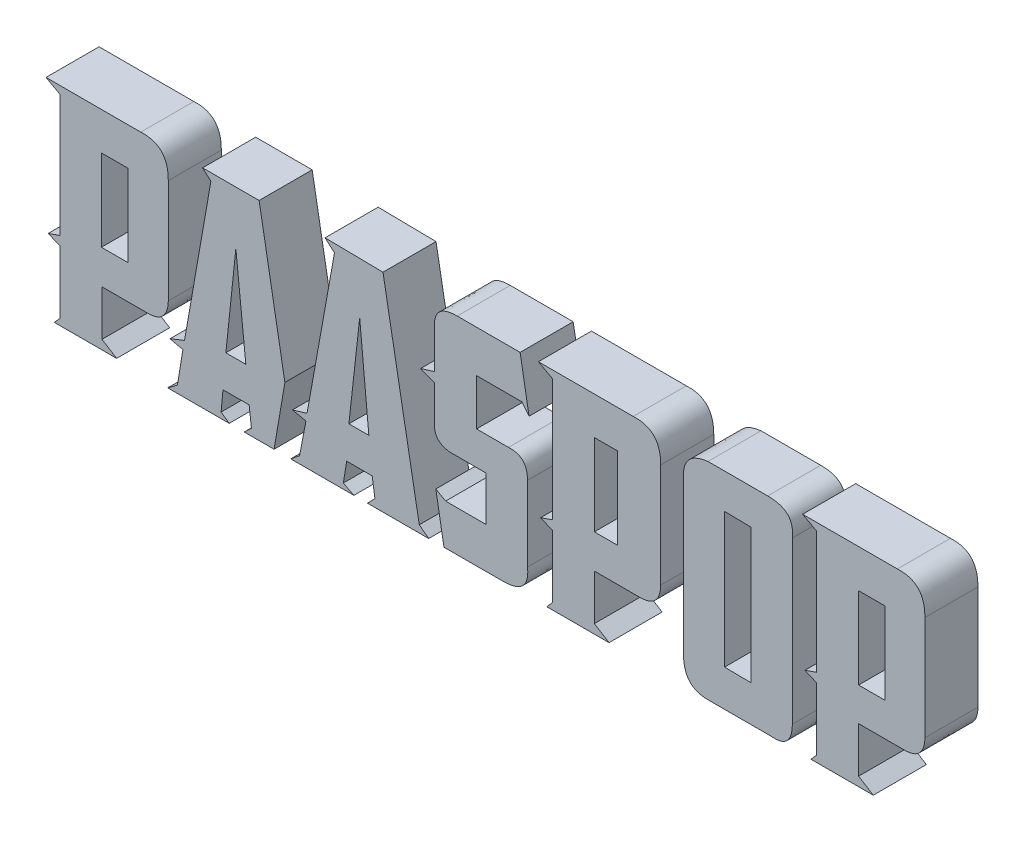
SolidWorks part; units mm, degrees
ref_plane "Front Plane" through (0, 0, 0) normal (0, 0, 1) x (1, 0, 0)
ref_plane "Top Plane" through (0, 0, 0) normal (0, 1, 0) x (1, 0, 0)
ref_plane "Right Plane" through (0, 0, 0) normal (1, 0, 0) x (0, 0, -1)
sketch "Model" plane through (0, 0, 0) normal (0, 0, 1) x (1, 0, 0)
  line L0 (89.8024, -74.6322) -> (88.2702, -65.8873)
  line L1 (88.2702, -65.8873) -> (90.1091, -66.95)
  line L2 (90.1091, -66.95) -> (97.75, -66.95)
  line L3 (97.75, -66.95) -> (97.75, -58.55)
  line L4 (97.75, -58.55) -> (90.9968, -58.55)
  line L5 (87.9813, -48.6879) -> (85.3918, -47.6707)
  line L6 (85.3918, -47.6707) -> (88.05, -46.8495)
  line L7 (88.05, -46.8495) -> (88.05, -39.9178)
  line L8 (104.1551, -35.65) -> (105.839, -45.2393)
  line L9 (105.839, -45.2393) -> (104.4684, -43.55)
  line L10 (104.4684, -43.55) -> (95.95, -43.55)
  line L11 (95.95, -43.55) -> (95.95, -52.25)
  line L12 (95.95, -52.25) -> (101.962, -52.25)
  line L13 (107.6013, -35.45) -> (125.459, -35.45)
  line L14 (118.15, -64.35) -> (118.15, -72.9269)
  line L15 (118.15, -72.9269) -> (120.9162, -74.65)
  line L16 (120.9162, -74.65) -> (109.1678, -74.65)
  line L17 (109.1678, -74.65) -> (110.25, -73.436)
  line L18 (110.25, -73.436) -> (110.25, -61.6483)
  line L19 (110.25, -61.6483) -> (108.0178, -60.7085)
  line L20 (108.0178, -60.7085) -> (110.25, -59.9252)
  line L21 (110.25, -59.9252) -> (110.25, -36.8982)
  line L22 (110.25, -36.8982) -> (107.6013, -35.45)
  line L23 (139.5572, -74.65) -> (151.4623, -74.65)
  line L24 (14.8013, -35.45) -> (32.659, -35.45)
  line L25 (25.35, -64.35) -> (25.35, -72.9269)
  line L26 (25.35, -72.9269) -> (28.1162, -74.65)
  line L27 (28.1162, -74.65) -> (16.3678, -74.65)
  line L28 (16.3678, -74.65) -> (17.45, -73.436)
  line L29 (17.45, -73.436) -> (17.45, -61.6483)
  line L30 (17.45, -61.6483) -> (15.2178, -60.7085)
  line L31 (15.2178, -60.7085) -> (17.45, -59.9252)
  line L32 (17.45, -59.9252) -> (17.45, -36.8982)
  line L33 (17.45, -36.8982) -> (14.8013, -35.45)
  line L34 (157.4013, -35.45) -> (175.259, -35.45)
  line L35 (167.95, -64.35) -> (167.95, -72.9269)
  line L36 (167.95, -72.9269) -> (170.7162, -74.65)
  line L37 (170.7162, -74.65) -> (158.9678, -74.65)
  line L38 (158.9678, -74.65) -> (160.05, -73.436)
  line L39 (160.05, -73.436) -> (160.05, -61.6483)
  line L40 (160.05, -61.6483) -> (157.8178, -60.7085)
  line L41 (157.8178, -60.7085) -> (160.05, -59.9252)
  line L42 (160.05, -59.9252) -> (160.05, -36.8982)
  line L43 (160.05, -36.8982) -> (157.4013, -35.45)
  line L44 (37.737, -74.65) -> (49.3288, -74.65)
  line L45 (49.3288, -74.65) -> (47.8015, -73.5707)
  line L46 (47.8015, -73.5707) -> (48.154, -69.75)
  line L47 (48.154, -69.75) -> (53.0883, -69.75)
  line L48 (53.0883, -69.75) -> (53.5191, -73.3748)
  line L49 (53.5191, -73.3748) -> (52.1485, -74.65)
  line L50 (52.1485, -74.65) -> (57.7877, -74.65)
  line L51 (57.7877, -74.65) -> (59.8241, -62.7257)
  line L52 (59.8241, -62.7257) -> (54.9681, -35.45)
  line L53 (54.9681, -35.45) -> (44.3161, -35.45)
  line L54 (44.3161, -35.45) -> (45.8826, -36.8399)
  line L55 (45.8826, -36.8399) -> (40.9091, -65.3199)
  line L56 (40.9091, -65.3199) -> (38.1678, -66.4213)
  line L57 (38.1678, -66.4213) -> (40.5958, -66.9719)
  line L58 (40.5958, -66.9719) -> (39.5776, -73.2781)
  line L59 (39.5776, -73.2781) -> (37.737, -74.65)
  line L60 (48.7022, -63.45) -> (52.4618, -63.45)
  line L61 (52.4618, -63.45) -> (50.582, -45.4879)
  line L62 (50.582, -45.4879) -> (48.7022, -63.45)
  line L63 (60.9207, -74.65) -> (72.8258, -74.65)
  line L64 (72.8258, -74.65) -> (70.8416, -73.6359)
  line L65 (70.8416, -73.6359) -> (71.4682, -69.75)
  line L66 (71.4682, -69.75) -> (76.272, -69.75)
  line L67 (76.272, -69.75) -> (76.7942, -73.1921)
  line L68 (76.7942, -73.1921) -> (75.3844, -74.65)
  line L69 (75.3844, -74.65) -> (86.924, -74.65)
  line L70 (86.924, -74.65) -> (85.1486, -73.2924)
  line L71 (85.1486, -73.2924) -> (78.3084, -35.4884)
  line L72 (78.3084, -35.4884) -> (67.3954, -35.3317)
  line L73 (67.3954, -35.3317) -> (69.1707, -36.8982)
  line L74 (69.1707, -36.8982) -> (64.0014, -65.6689)
  line L75 (64.0014, -65.6689) -> (61.234, -66.5044)
  line L76 (61.234, -66.5044) -> (63.7925, -67.0265)
  line L77 (63.7925, -67.0265) -> (62.5916, -73.2924)
  line L78 (62.5916, -73.2924) -> (60.9207, -74.65)
  line L79 (71.8859, -63.45) -> (75.6454, -63.45)
  line L80 (75.6454, -63.45) -> (73.9223, -45.1224)
  line L81 (73.9223, -45.1224) -> (71.8859, -63.45)
  line L82 (118.15, -42.55) -> (118.15, -57.95)
  line L83 (118.15, -57.95) -> (122.55, -57.95)
  line L84 (122.55, -57.95) -> (122.55, -42.55)
  line L85 (122.55, -42.55) -> (118.15, -42.55)
  line L86 (142.6901, -67.7519) -> (147.6897, -67.8136)
  line L87 (147.6897, -67.8136) -> (147.6897, -42.4117)
  line L88 (147.6897, -42.4117) -> (142.6901, -42.35)
  line L89 (142.6901, -42.35) -> (142.6901, -67.7519)
  line L90 (25.25, -42.55) -> (25.25, -57.95)
  line L91 (25.25, -57.95) -> (30.25, -57.95)
  line L92 (30.25, -57.95) -> (30.25, -42.55)
  line L93 (30.25, -42.55) -> (25.25, -42.55)
  line L94 (167.95, -42.65) -> (167.95, -58.05)
  line L95 (167.95, -58.05) -> (172.95, -58.05)
  line L96 (172.95, -58.05) -> (172.95, -42.65)
  line L97 (172.95, -42.65) -> (167.95, -42.65)
  spline S0 degree 2 poles (90.9968, -58.55) (88.0205, -58.2803) (87.9813, -55.5389) knots 5 5 5 6 6 6
  spline S1 degree 2 poles (87.9813, -55.5389) (87.9422, -52.7976) (87.9813, -48.6879) knots 6 6 6 7 7 7
  spline S2 degree 2 poles (88.05, -39.9178) (87.5897, -35.65) (92.2891, -35.65) knots 10 10 10 11 11 11
  spline S3 degree 2 poles (92.2891, -35.65) (96.9885, -35.65) (104.1551, -35.65) knots 11 11 11 12 12 12
  spline S4 degree 2 poles (101.962, -52.25) (105.55, -52.0579) (105.55, -55.837) knots 17 17 17 18 18 18
  spline S5 degree 2 poles (105.55, -55.837) (105.55, -59.6161) (105.55, -69.994) knots 18 18 18 19 19 19
  spline S6 degree 2 poles (105.55, -69.994) (106.0665, -74.615) (100.9364, -74.615) knots 19 19 19 20 20 20
  spline S7 degree 2 poles (100.9364, -74.615) (95.8062, -74.615) (89.8024, -74.6322) knots 20 20 20 21 21 21
  spline S8 degree 2 poles (125.459, -35.45) (130.65, -35.1751) (130.65, -40.7752) knots 1 1 1 2 2 2
  spline S9 degree 2 poles (130.65, -40.7752) (130.65, -46.3753) (130.65, -60.3952) knots 2 2 2 3 3 3
  spline S10 degree 2 poles (130.65, -60.3952) (130.55, -64.35) (126.7513, -64.35) knots 3 3 3 4 4 4
  spline S11 degree 2 poles (126.7513, -64.35) (122.9526, -64.35) (118.15, -64.35) knots 4 4 4 5 5 5
  spline S12 degree 2 poles (151.4623, -74.65) (155.45, -75.0544) (155.45, -70.6944) knots 1 1 1 2 2 2
  spline S13 degree 2 poles (155.45, -70.6944) (155.45, -66.3344) (155.45, -40.3311) knots 2 2 2 3 3 3
  spline S14 degree 2 poles (155.45, -40.3311) (156.005, -35.75) (150.8096, -35.75) knots 3 3 3 4 4 4
  spline S15 degree 2 poles (150.8096, -35.75) (145.6142, -35.75) (139.5572, -35.75) knots 4 4 4 5 5 5
  spline S16 degree 2 poles (139.5572, -35.75) (134.95, -36.3105) (134.95, -40.2006) knots 5 5 5 6 6 6
  spline S17 degree 2 poles (134.95, -40.2006) (134.95, -44.0907) (134.95, -69.7807) knots 6 6 6 7 7 7
  spline S18 degree 2 poles (134.95, -69.7807) (135.0666, -74.65) (139.5572, -74.65) knots 7 7 7 8 8 8
  spline S19 degree 2 poles (32.659, -35.45) (37.85, -35.1751) (37.85, -40.7752) knots 1 1 1 2 2 2
  spline S20 degree 2 poles (37.85, -40.7752) (37.85, -46.3753) (37.85, -60.3952) knots 2 2 2 3 3 3
  spline S21 degree 2 poles (37.85, -60.3952) (37.75, -64.35) (33.9513, -64.35) knots 3 3 3 4 4 4
  spline S22 degree 2 poles (33.9513, -64.35) (30.1526, -64.35) (25.35, -64.35) knots 4 4 4 5 5 5
  spline S23 degree 2 poles (175.259, -35.45) (180.45, -35.1751) (180.45, -40.7752) knots 1 1 1 2 2 2
  spline S24 degree 2 poles (180.45, -40.7752) (180.45, -46.3753) (180.45, -60.3952) knots 2 2 2 3 3 3
  spline S25 degree 2 poles (180.45, -60.3952) (180.35, -64.35) (176.5513, -64.35) knots 3 3 3 4 4 4
  spline S26 degree 2 poles (176.5513, -64.35) (172.7526, -64.35) (167.95, -64.35) knots 4 4 4 5 5 5
extrude "Boss-Extrude1" add sketch "Model" along normal blind 10
